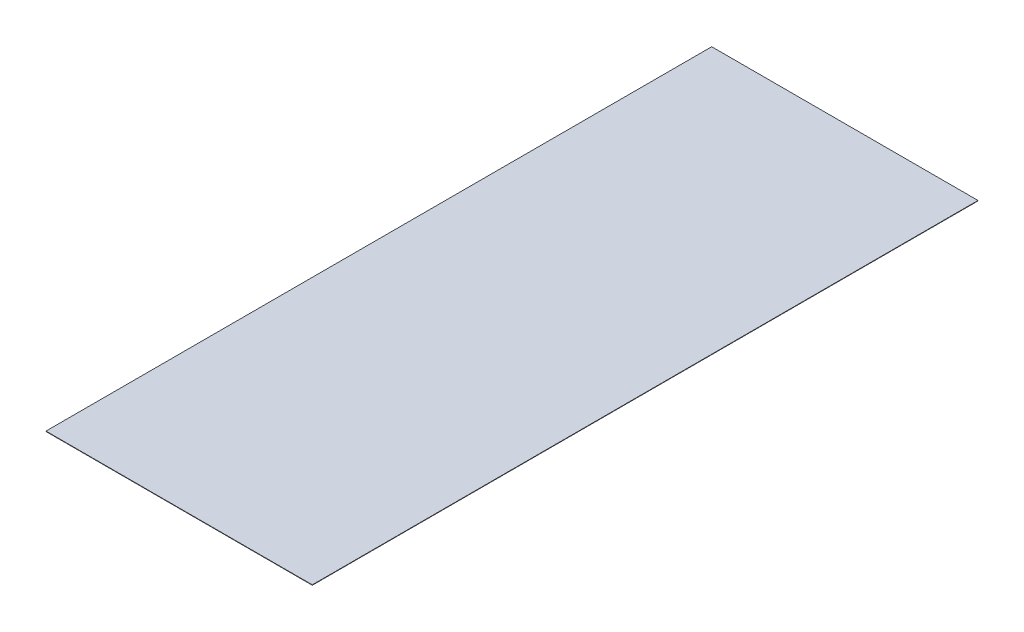
SolidWorks part; units mm, degrees
material "ASTM A36 Acero"
ref_plane "Alzado" through (0, 0, 0) normal (0, 0, 1) x (1, 0, 0)
ref_plane "Planta" through (0, 0, 0) normal (0, 1, 0) x (1, 0, 0)
ref_plane "Vista lateral" through (0, 0, 0) normal (1, 0, 0) x (0, 0, -1)
sketch "Croquis1" plane through (0, 0, 0) normal (0, 1, 0) x (1, 0, 0)
  line L1 (-609.6, -1524) -> (609.6, -1524)
  line L2 (-609.6, -1524) -> (-609.6, 1524)
  line L3 (-609.6, 1524) -> (609.6, 1524)
  line L4 (609.6, -1524) -> (609.6, 1524)
  line L5 (-609.6, -1524) -> (609.6, 1524) construction
  line L6 (-609.6, 1524) -> (609.6, -1524) construction
  point P0 (0, 0)
  dimension "D1" = 3048
  dimension "D2" = 1219.2
extrude "Saliente-Extruir1" add sketch "Croquis1" along normal blind 1.9
